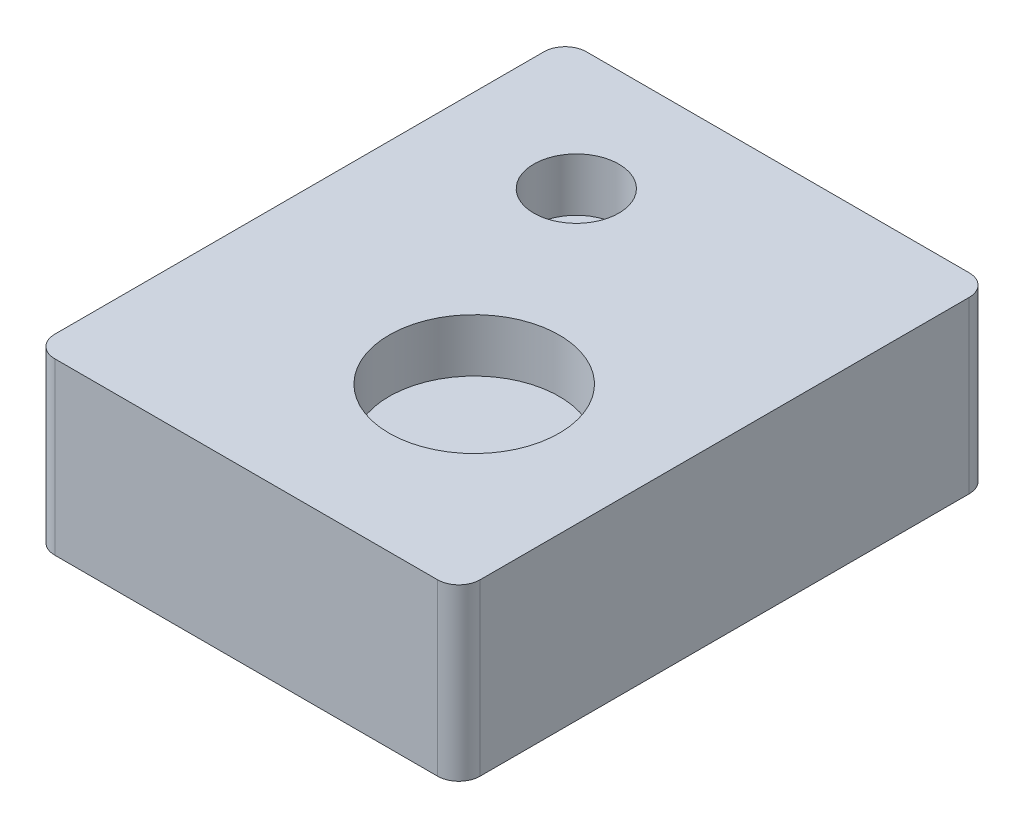
SolidWorks part; units mm, degrees
material "Custom Plastic"
ref_plane "Front Plane" through (0, 0, 0) normal (0, 0, 1) x (1, 0, 0)
ref_plane "Top Plane" through (0, 0, 0) normal (0, 1, 0) x (1, 0, 0)
ref_plane "Right Plane" through (0, 0, 0) normal (1, 0, 0) x (0, 0, -1)
sketch "Sketch1" plane through (0, 0, 0) normal (0, 1, 0) x (1, 0, 0)
  line L1 (-8.1383, 7.4468) -> (11.8617, 7.4468)
  line L2 (-8.1383, 7.4468) -> (-8.1383, -17.5532)
  line L3 (-8.1383, -17.5532) -> (11.8617, -17.5532)
  line L4 (11.8617, 7.4468) -> (11.8617, -17.5532)
  dimension "D1" = 20
  dimension "D2" = 25
extrude "Boss-Extrude1" add sketch "Sketch1" along normal blind 8 contours L2 L3 L4 L1
fillet "Fillet1" radius 1 4 edges at (11.8617, 4, 17.5532) (11.8617, 4, -7.4468) (-8.1383, 4, -7.4468) (-8.1383, 4, 17.5532)
sketch "Sketch3" plane through (0, 8, 0) normal (0, 1, 0) x (1, 0, 0)
  line L14 (-6.6383, 5.9468) -> (10.3617, 5.9468)
  line L15 (10.3617, 5.9468) -> (10.3617, -16.0532)
  line L16 (-6.6383, -16.0532) -> (10.3617, -16.0532)
  line L17 (-6.6383, 5.9468) -> (-6.6383, -16.0532)
sketch "Sketch4" plane through (0, 8, 0) normal (0, 1, 0) x (1, 0, 0)
  circle A0 centre (-1.804, 1.6367) radius 2
  circle A1 centre (3.7559, -8.725) radius 4
  dimension "D1" = 4
  dimension "D2" = 8
extrude "Cut-Extrude1" cut sketch "Sketch4" against normal blind 2.5
